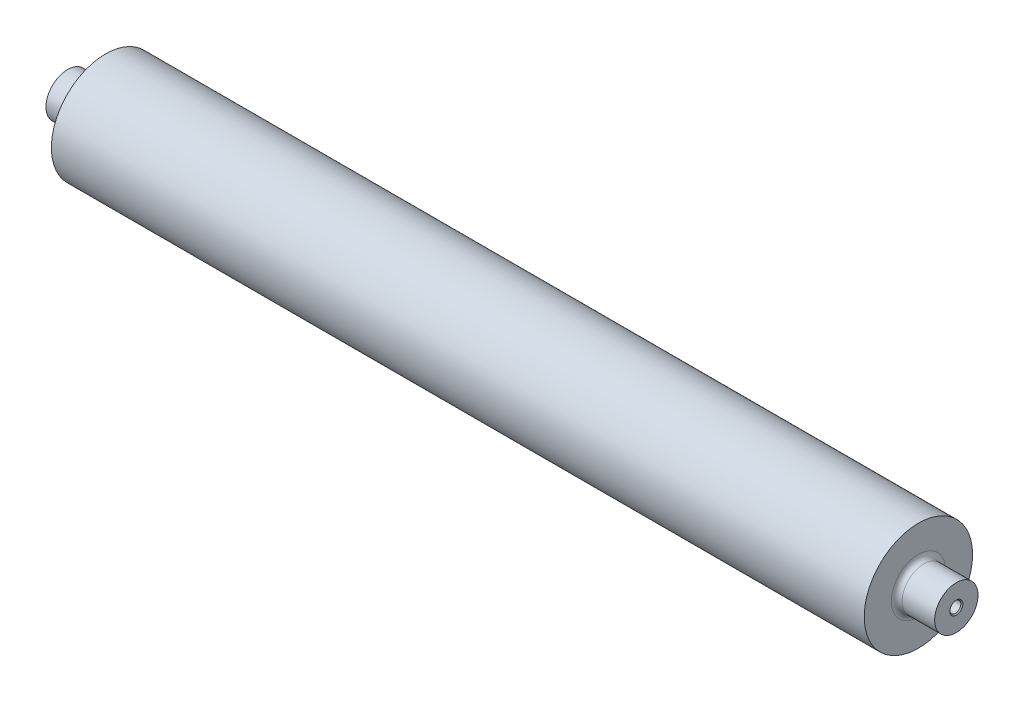
SolidWorks part; units mm, degrees
ref_plane "Front Plane" through (0, 0, 0) normal (0, 0, 1) x (1, 0, 0)
ref_plane "Top Plane" through (0, 0, 0) normal (0, 1, 0) x (1, 0, 0)
ref_plane "Right Plane" through (0, 0, 0) normal (1, 0, 0) x (0, 0, -1)
sketch "Sketch1" plane through (0, 0, 0) normal (0, 0, 1) x (1, 0, 0)
  line L0 (0, 0) -> (0, 20)
  line L1 (0, -55) -> (0, 55) construction
  line L2 (0, 20) -> (35, 20)
  line L3 (35, 20) -> (35, 50)
  line L4 (35, 50) -> (785, 50)
  line L5 (785, 50) -> (785, 20)
  line L6 (785, 20) -> (820, 20)
  line L7 (820, 20) -> (820, 0)
  line L8 (55, 0) -> (-55, 0) construction
  line L9 (820, 0) -> (0, 0)
  dimension "D1" = 20
  dimension "D2" = 35
  dimension "D3" = 820
  dimension "D4" = 750
  dimension "D5" = 50
revolve "Revolve1" add sketch "Sketch1" angle 360 about L9
fillet "Fillet1" radius 5 2 edges at (785, 0, -20) (35, 0, -20)
hole_wizard "M12 Tapped Hole4" positions "3DSketch12" profile "Sketch19" tap size "M12" standard "ISO"
sketch3d "3DSketch12"
  circle A0 centre (820, 0, 0) radius 20 construction
  point P0 (0, 0, 0)
  point P2 (820, 0, 0)
  point P7 (840, 0, 0)
  dimension "D1" = 0
  dimension "D2" = 0
sketch "Sketch19" plane through (0, 0, 0) normal (0, 1, 0) x (0, 0, 1)
  line L0 (0, 0) -> (0, 32.3144)
  line L1 (0, 32.3144) -> (5.1, 29.25)
  line L2 (5.1, 29.25) -> (5.1, 0.925)
  line L3 (5.1, 0.925) -> (6.025, 0)
  line L5 (6.025, 0) -> (0, 0)
  line L6 (-5.1, 0.925) -> (-6.025, 0) construction
  line L10 (0, 32.3144) -> (-5.1, 29.25) construction
  line L11 (0, -6.35) -> (0, 107.95) construction
  dimension "Tap Drill Dia." = 10.2
  dimension "Tap Drill Depth" = 29.25
  dimension "Near C'Sink Dia." = 12.05
  dimension "Near C'Sink Angle" = 90
  dimension "Drill Angle" = 118
